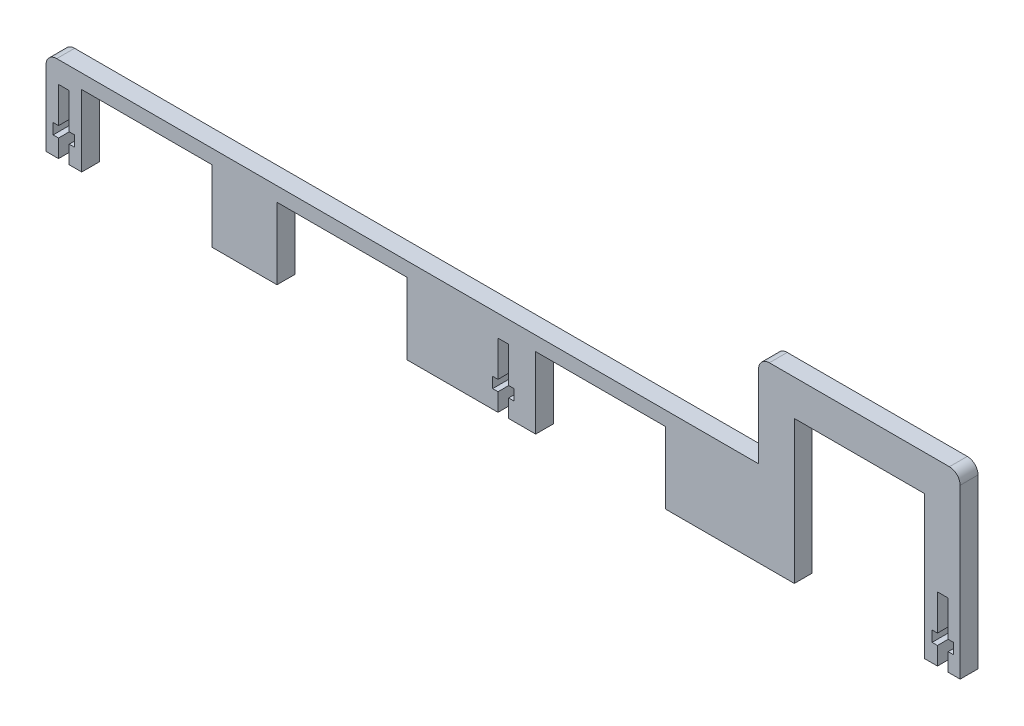
SolidWorks part; units mm, degrees
ref_plane "Front Plane" through (0, 0, 0) normal (0, 0, 1) x (1, 0, 0)
ref_plane "Top Plane" through (0, 0, 0) normal (0, 1, 0) x (1, 0, 0)
ref_plane "Right Plane" through (0, 0, 0) normal (1, 0, 0) x (0, 0, -1)
sketch "Esquisse1" plane through (0, 0, 0) normal (0, 0, 1) x (1, 0, 0)
  line L0 (0, 0) -> (0, 21)
  line L3 (64.65, 0) -> (46.4, 0)
  line L4 (46.4, 0) -> (46.4, 20)
  line L5 (46.4, 20) -> (10, 20)
  line L6 (10, 20) -> (10, 0)
  line L7 (10, 0) -> (0, 0)
  line L8 (64.65, 24) -> (64.65, 0) construction
  line L9 (64.65, 0) -> (64.65, 20)
  line L10 (64.65, 20) -> (101.05, 20)
  line L11 (101.05, 20) -> (101.05, 0)
  line L12 (101.05, 0) -> (137.05, 0)
  line L13 (137.05, 0) -> (137.05, 20)
  line L14 (137.05, 20) -> (173.45, 20)
  line L15 (173.45, 20) -> (173.45, 0)
  line L16 (173.45, 0) -> (209.45, 0)
  line L18 (3, 24) -> (199.45, 24)
  line L19 (199.45, 24) -> (199.45, 47)
  line L20 (202.45, 50) -> (252.85, 50)
  line L21 (255.85, 47) -> (255.85, 0)
  line L24 (209.45, 0) -> (209.45, 40)
  line L25 (209.45, 40) -> (245.85, 40)
  line L26 (245.85, 40) -> (245.85, 0)
  line L27 (245.85, 0) -> (255.85, 0)
  arc A0 (0, 21) -> (3, 24) centre (3, 21) cw
  arc A1 (255.85, 47) -> (252.85, 50) centre (252.85, 47) ccw
  arc A2 (199.45, 47) -> (202.45, 50) centre (202.45, 47) cw
  point P20 (197.8503, 51.1779)
  point P24 (201.8152, 52.6712)
  point P25 (255.1744, 52.5795)
  dimension "D9" = 3
  dimension "D18" = 3
  dimension "D1" = 36.4
  dimension "D2" = 10
  dimension "D3" = 18.25
  dimension "D4" = 4
  dimension "D5" = 20
  dimension "D6" = 4
  dimension "D7" = 36
  dimension "D8" = 36
  dimension "D10" = 36.4
  dimension "D11" = 36.4
  dimension "D12" = 20
  dimension "D13" = 40
  dimension "D14" = 36.4
  dimension "D15" = 10
  dimension "D16" = 10
  dimension "D17" = 10
extrude "Boss.-Extru.1" add sketch "Esquisse1" along normal blind 5
sketch "Esquisse2" plane through (0, 0, 5) normal (0, 0, 1) x (1, 0, 0)
  line L0 (5, 0) -> (5, 18) construction
  line L1 (0, 0) -> (10, 0) construction
  line L2 (6.5, 0) -> (6.5, 5)
  line L3 (6.5, 5) -> (8, 5)
  line L4 (8, 5) -> (8, 8)
  line L5 (8, 8) -> (6.5, 8)
  line L6 (6.5, 8) -> (6.5, 18)
  line L7 (6.5, 18) -> (3.5, 18)
  line L8 (3.5, 8) -> (3.5, 18)
  line L9 (2, 8) -> (3.5, 8)
  line L10 (2, 5) -> (2, 8)
  line L11 (3.5, 5) -> (2, 5)
  line L12 (3.5, 0) -> (3.5, 5)
  line L13 (3.5, 0) -> (6.5, 0)
  point P4 (5, 0)
  dimension "D1" = 3
  dimension "D2" = 3
  dimension "D3" = 6
  dimension "D4" = 3
  dimension "D5" = 18
  dimension "D6" = 5
extrude "Enlèv. mat.-Extru.2" cut sketch "Esquisse2" against normal blind 5
pattern_linear "Répétition linéaire1" count 3 spacing 123 along (1, 0, 0) of "Enlèv. mat.-Extru.2"
